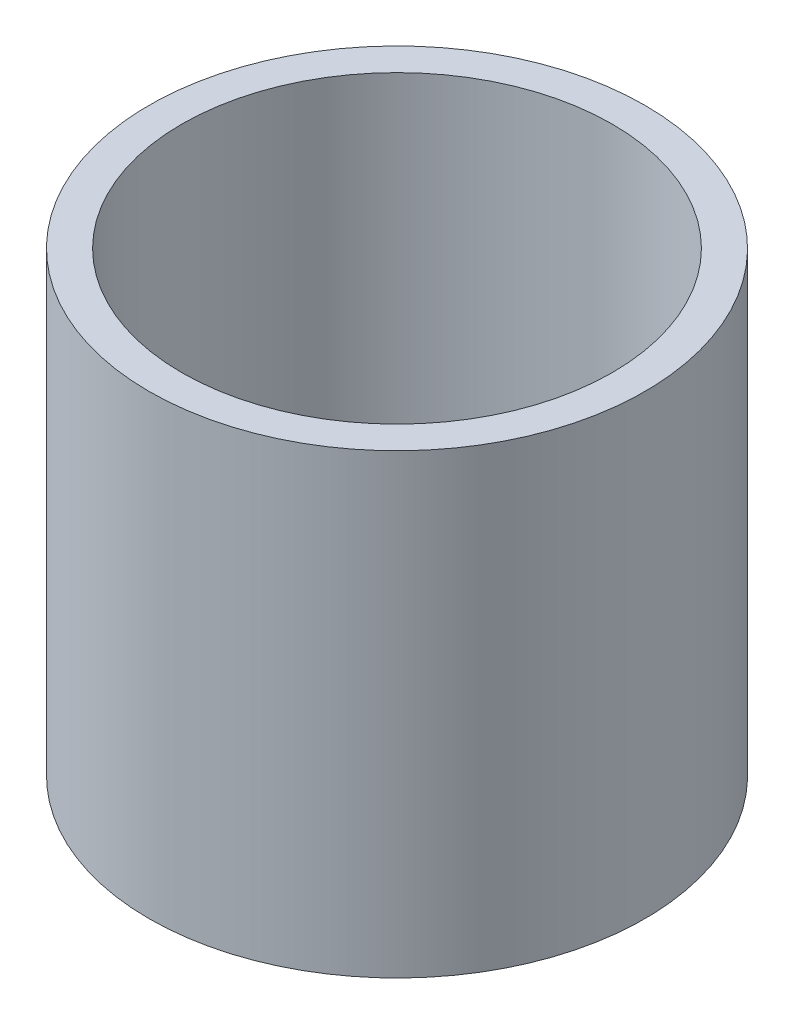
SolidWorks part; units mm, degrees
ref_plane "Спереди" through (0, 0, 0) normal (0, 0, 1) x (1, 0, 0)
ref_plane "Сверху" through (0, 0, 0) normal (0, 1, 0) x (1, 0, 0)
ref_plane "Справа" through (0, 0, 0) normal (1, 0, 0) x (0, 0, -1)
sketch "Эскиз1" plane through (0, 0, 0) normal (0, 1, 0) x (1, 0, 0)
  circle A0 centre (0, 0) radius 19
  dimension "D1" = 38
extrude "Бобышка-Вытянуть1" add sketch "Эскиз1" along normal blind 5
sketch "Эскиз2" plane through (0, 5, 0) normal (0, 1, 0) x (1, 0, 0)
  circle A0 centre (0, 0) radius 19
  circle A1 centre (0, 0) radius 16.5
  circle A2 centre (0, 0) radius 19 construction
  dimension "D1" = 33
  dimension "D2" = 0
extrude "Бобышка-Вытянуть2" add sketch "Эскиз2" along normal blind 30
